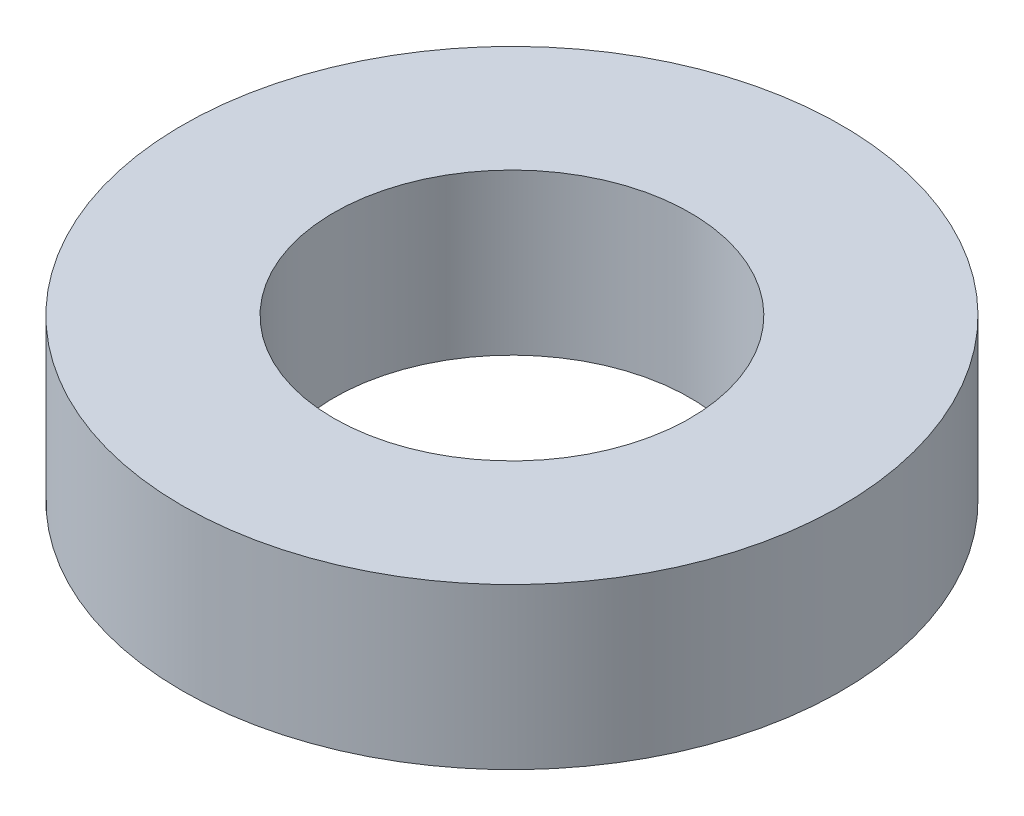
SolidWorks part; units mm, degrees
ref_plane "Plan de face" through (0, 0, 0) normal (0, 0, 1) x (1, 0, 0)
ref_plane "Plan de dessus" through (0, 0, 0) normal (0, 1, 0) x (1, 0, 0)
ref_plane "Plan de droite" through (0, 0, 0) normal (1, 0, 0) x (0, 0, -1)
sketch "Esquisse1" plane through (0, 0, 0) normal (0, 1, 0) x (1, 0, 0)
  circle A0 centre (0, 0) radius 18.5
extrude "Boss.-Extru.1" add sketch "Esquisse1" along normal blind 9
sketch "Esquisse2" plane through (0, 9, 0) normal (0, 1, 0) x (1, 0, 0)
  circle A0 centre (0, 0) radius 10
extrude "Enlèv. mat.-Extru.1" cut sketch "Esquisse2" against normal blind 9
